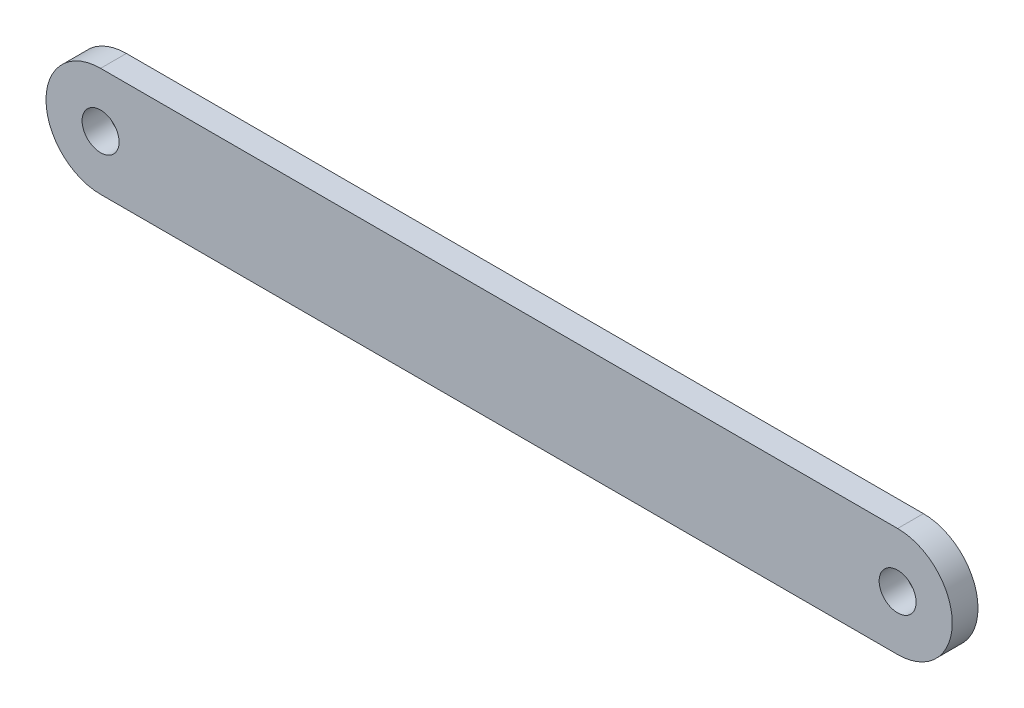
SolidWorks part; units mm, degrees
material "Custom Plastic"
ref_plane "Front Plane" through (0, 0, 0) normal (0, 0, 1) x (1, 0, 0)
ref_plane "Top Plane" through (0, 0, 0) normal (0, 1, 0) x (1, 0, 0)
ref_plane "Right Plane" through (0, 0, 0) normal (1, 0, 0) x (0, 0, -1)
sketch "Sketch1" plane through (0, 0, 0) normal (0, 0, 1) x (1, 0, 0)
  line L0 (-46.355, 0) -> (46.355, 0) construction
  line L1 (-46.355, 6.35) -> (46.355, 6.35)
  line L2 (-46.355, -6.35) -> (46.355, -6.35)
  arc A0 (-46.355, 6.35) -> (-46.355, -6.35) centre (-46.355, 0) ccw
  arc A1 (46.355, -6.35) -> (46.355, 6.35) centre (46.355, 0) ccw
  point P3 (0, 0)
  dimension "D1" = 6.35
  dimension "D2" = 92.71
extrude "Boss-Extrude1" add sketch "Sketch1" along normal blind 2.9972
hole_wizard "#8 Clearance Hole1" positions "Sketch3" profile "Sketch2" hole size "#8" standard "ANSI Inch"
sketch "Sketch3" plane through (0, 0, 2.9972) normal (0, 0, 1) x (1, 0, 0)
  point P0 (-46.355, 0)
  point P3 (46.355, 0)
sketch "Sketch2" plane through (-46.355, 0, 2.9972) normal (1, 0, 0) x (0, -1, 0)
  line L0 (0, 0) -> (0, 6.351)
  line L1 (0, 6.351) -> (2.1526, 6.351)
  line L2 (2.1526, 6.351) -> (2.1526, 0)
  line L5 (2.1526, 0) -> (0, 0)
  line L10 (0, 6.351) -> (-2.1526, 6.351) construction
  line L11 (0, -6.35) -> (0, 107.95) construction
  dimension "Hole Dia." = 4.3053
  dimension "Hole Depth" = 6.351
  dimension "Drill Angle" = 180
sketch "Sketch4" plane through (0, 0, 0) normal (0, 0, -1) x (-1, 0, 0)
  line L0 (-28.8293, -6.35) -> (-41.5293, -6.35)
  line L1 (46.355, -6.35) -> (-46.355, -6.35) construction
  line L2 (-41.5293, -6.35) -> (-43.2155, -12.472)
  line L3 (-43.2155, -12.472) -> (-28.8293, -6.35)
  circle A0 centre (-46.355, 0) radius 6.35 construction
  circle A1 centre (-46.355, 0) radius 2.1526 construction
  dimension "D4" = 12.7
  dimension "D1" = 12.7
  dimension "D2" = 105.4
  dimension "D3" = 6.35
  dimension "D5" = 7.9756
extrude "Hard stop" [suppressed] add sketch "Sketch4" against normal blind 2.9972
